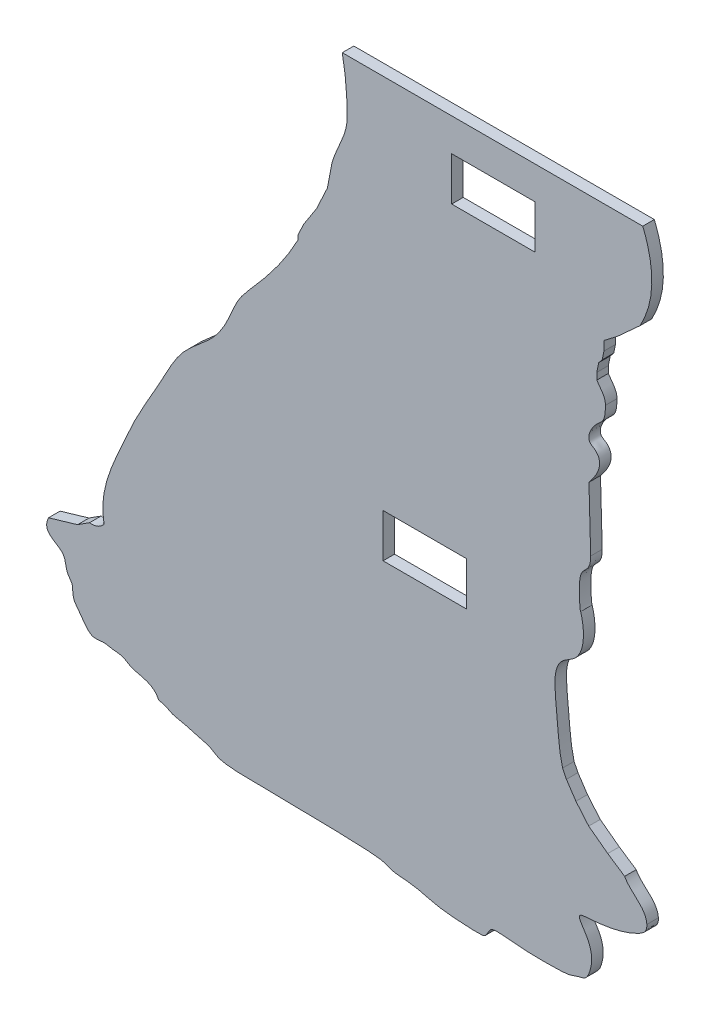
SolidWorks part; units mm, degrees
ref_plane "Front Plane" through (0, 0, 0) normal (0, 0, 1) x (1, 0, 0)
ref_plane "Top Plane" through (0, 0, 0) normal (0, 1, 0) x (1, 0, 0)
ref_plane "Right Plane" through (0, 0, 0) normal (1, 0, 0) x (0, 0, -1)
sketch "Sketch1" plane through (0, 0, 0) normal (0, 0, 1) x (1, 0, 0)
  line L0 (134.6667, 500.5) -> (673.3333, 500.5) construction
  line L2 (167.2022, 42.2012) -> (162.5517, 45.3095)
  line L3 (162.5517, 45.3095) -> (157.3147, 49.2233)
  line L4 (157.3147, 49.2233) -> (153.7929, 53.3936)
  line L5 (153.7929, 53.3936) -> (151.1787, 57.3127)
  line L6 (151.1787, 57.3127) -> (150.1126, 59.4633)
  line L7 (157.3755, 131.2295) -> (157.854, 113.8805)
  line L8 (159.5344, 156.6595) -> (159.5344, 158.498)
  line L9 (159.5344, 158.498) -> (160.0825, 161.1123)
  line L10 (160.0825, 161.1123) -> (161.0243, 162.2425)
  line L11 (161.0243, 162.2425) -> (161.5128, 164.5724)
  line L12 (161.5128, 164.5724) -> (161.5128, 167.1023)
  line L13 (161.5128, 167.1023) -> (165.1835, 169.9013)
  line L14 (165.1835, 169.9013) -> (171.472, 175.6217)
  line L15 (86.5908, 171.7678) -> (85.3882, 165.3811)
  line L16 (89.473, 199.6877) -> (172.1964, 199.6877)
  line L17 (85.3882, 165.3811) -> (82.4023, 158.9826)
  line L18 (82.4023, 158.9826) -> (78.8266, 153.4325)
  line L19 (78.8266, 153.4325) -> (77.3096, 150.1819)
  line L20 (77.3096, 150.1819) -> (77.3096, 148.973)
  line L21 (89.473, 199.6877) -> (189.494, 199.6877) construction
  line L22 (127.4919, 8.5553) -> (214.3131, 8.5553) construction
  line L23 (8.6124, 48.3831) -> (8.6124, -14.4171) construction
  line L24 (173.32, 33.793) -> (173.32, -11.6797) construction
  line L34 (100.7031, 96.1631) -> (123.7031, 96.1631)
  line L35 (100.7031, 96.1631) -> (100.7031, 84.1631)
  line L36 (100.7031, 84.1631) -> (123.7031, 84.1631)
  line L37 (123.7031, 96.1631) -> (123.7031, 84.1631)
  line L38 (119.5917, 190.6583) -> (142.5917, 190.6583)
  line L39 (119.5917, 190.6583) -> (119.5917, 178.6583)
  line L40 (119.5917, 178.6583) -> (142.5917, 178.6583)
  line L41 (142.5917, 190.6583) -> (142.5917, 178.6583)
  spline S0 degree 1 poles (8.6124, 48.3831) (16.6111, 50.7357) knots 0 0 1 1
  spline S1 degree 1 poles (19.9047, 52.853) (16.6111, 50.7357) knots 0 0 1 1
  spline S2 degree 3 poles (23.9041, 54.4997) (22.542, 62.0444) (27.1512, 71.7199) (33.1716, 85.6736) (39.4703, 95.7444) (45.0444, 107.3971) (54.1548, 113.0729) (58.3579, 120.6747) (60.6418, 126.7915) (68.4166, 135.2748) (73.9208, 142.4894) (77.3096, 148.973) knots 0 0 0 0 0.194457 0.285904 0.412664 0.517827 0.629269 0.691339 0.750377 0.804905 1 1 1 1
  spline S3 degree 2 poles (19.9047, 52.853) (22.4371, 52.6083) (23.9041, 54.4997) knots 0 0 0 1 1 1
  spline S4 degree 3 poles (8.6124, 48.3831) (6.5691, 43.9628) (13.6478, 43.7296) (13.2535, 37.9915) (15.2259, 36.1128) (15.2445, 34.2074) (15.4257, 32.4092) (16.9812, 30.3171) (18.455, 28.2086) (20.7273, 25.6089) (23.6404, 26.5196) (26.3788, 25.705) (29.0077, 25.795) (31.226, 24.0079) (34.9468, 23.3493) (38.0007, 22.2222) (38.8831, 20.145) knots 0 0 0 0 0.18572 0.273851 0.320038 0.350192 0.393849 0.435551 0.514834 0.569195 0.638874 0.687587 0.755837 0.801068 0.865551 1 1 1 1
  spline S5 degree 3 poles (38.8831, 20.145) (41.2875, 19.5656) (42.3458, 18.5073) (45.4199, 18.1546) (49.7538, 16.7939) (52.7775, 16.1892) (54.7934, 14.8285) (56.3556, 14.1734) (60.1352, 13.7702) (61.5463, 13.7702) (99.2418, 13.2159) (101.2856, 12.2232) (103.9594, 11.2977) (106.3246, 11.2977) (111.5693, 10.5778) (115.1686, 9.2409) (123.9098, 8.5211) (128.0233, 8.5211) (128.9488, 8.7267) (129.9772, 10.7835) (131.0055, 11.8119) (139.3353, 10.7835) (144.7857, 10.7835) (151.9843, 10.7835) (154.3496, 12.1204) (156.7148, 12.1204) (158.1545, 16.0282) (158.1545, 19.319) (157.3318, 21.6842) (156.4063, 23.3296) (153.7325, 27.1346) (157.3189, 27.1346) (163.0629, 27.7755) (167.4392, 28.9243) (170.3933, 30.1004) (172.4447, 31.2857) (173.2037, 32.3228) (173.32, 33.1913) (173.32, 33.793) knots 0 0 0 0 0.028571 0.057143 0.085714 0.114286 0.142857 0.171429 0.2 0.228571 0.257143 0.285714 0.314286 0.342857 0.371429 0.4 0.428571 0.457143 0.485714 0.514286 0.542857 0.571429 0.6 0.628571 0.657143 0.685714 0.714286 0.742857 0.771429 0.8 0.828571 0.857143 0.885714 0.914286 0.942857 0.971429 0.985714 1 1 1 1
  spline S6 degree 3 poles (173.32, 33.793) (173.0564, 37.6266) (168.8406, 39.1122) (167.2022, 42.2012) knots 0 0 0 0 1 1 1 1
  spline S7 degree 3 poles (150.1126, 59.4633) (148.9568, 63.837) (148.9486, 71.4394) (146.8505, 84.0514) (156.4694, 88.1502) (156.2475, 95.5102) (155.0853, 99.2556) knots 0 0 0 0 0.308783 0.618237 0.704406 1 1 1 1
  spline S8 degree 3 poles (157.854, 113.8805) (157.8564, 113.8699) (157.8506, 110.688) (155.3081, 109.3846) (154.4188, 105.0533) (154.8696, 99.4834) (155.0853, 99.2556) knots 0 0 0 0 0.124799 0.365608 0.555267 1 1 1 1
  spline S9 degree 3 poles (161.8927, 151.8072) (161.9125, 149.0313) (161.4499, 147.7916) (158.4451, 145.386) (156.1309, 141.3803) (158.8302, 140.0435) (161.6487, 137.4079) (159.4597, 133.7277) (157.3755, 131.2295) knots 0 0 0 0 0.190659 0.228613 0.488803 0.534056 0.585176 1 1 1 1
  spline S10 degree 3 poles (159.5344, 156.6595) (160.7867, 154.8399) (162.0055, 153.6124) (161.8927, 151.8072) knots 0 0 0 0 1 1 1 1
  spline S11 degree 2 poles (172.1964, 199.6877) (177.5125, 186.6119) (171.472, 175.6217) knots 0 0 0 1 1 1
  spline S12 degree 3 poles (89.473, 199.6877) (90.4497, 194.8375) (90.826, 189.8378) (90.8383, 180.2807) (87.6783, 176.1914) (86.5908, 171.7678) knots 0 0 0 0 0.517811 0.520823 1 1 1 1
  point P126 (91.6663, 180.6353)
  dimension "D3" = 12
  dimension "D1" = 23
  dimension "D2" = 164.7075
  dimension "D4" = 23
  dimension "D5" = 12
extrude "Boss-Extrude2" add sketch "Sketch1" along normal blind 3.175
